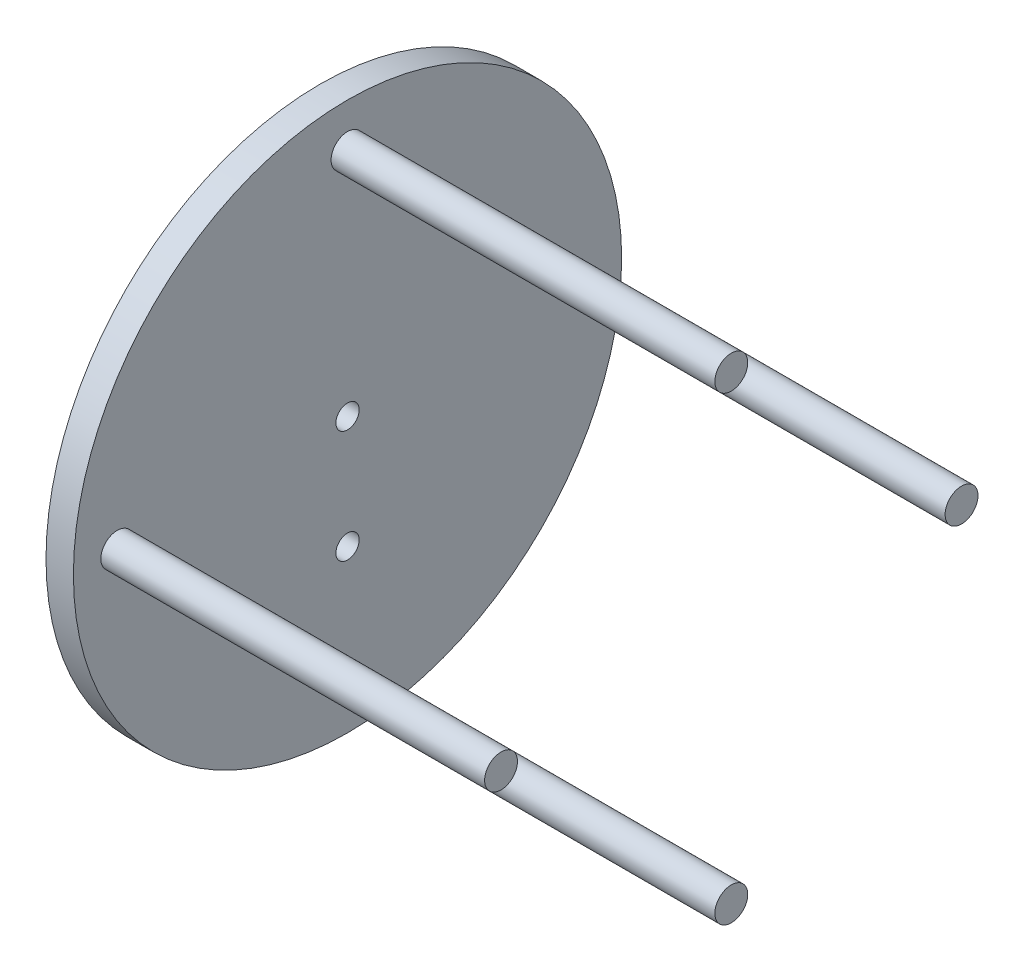
SolidWorks part; units mm, degrees
ref_plane "Plan de face" through (0, 0, 0) normal (0, 0, 1) x (1, 0, 0)
ref_plane "Plan de dessus" through (0, 0, 0) normal (0, 1, 0) x (1, 0, 0)
ref_plane "Plan de droite" through (0, 0, 0) normal (1, 0, 0) x (0, 0, -1)
sketch "Esquisse1" plane through (0, 0, 0) normal (1, 0, 0) x (0, 0, -1)
  circle A0 centre (0, 0) radius 50
  dimension "D1" = 100
extrude "Boss.-Extru.1" add sketch "Esquisse1" along normal blind 5
sketch "Esquisse2" plane through (5, 0, 0) normal (1, 0, 0) x (0, 0, -1)
  line L0 (0, 0) -> (50, 0) construction
  line L1 (0, 0) -> (-50, 0) construction
  line L2 (0, 0) -> (0, 50) construction
  line L3 (0, 0) -> (0, -50) construction
  circle A0 centre (0, 0) radius 50 construction
  circle A1 centre (-42, 0) radius 3
  circle A2 centre (42, 0) radius 3
  circle A3 centre (0, -42) radius 3
  circle A4 centre (0, 42) radius 3
  dimension "D3" = 6
  dimension "D4" = 6
  dimension "D7" = 6
  dimension "D8" = 6
  dimension "D1" = 8
  dimension "D2" = 8
  dimension "D5" = 8
  dimension "D6" = 8
extrude "Boss.-Extru.3" add sketch "Esquisse2" along normal blind 70
sketch "Esquisse3" plane through (5, 0, 0) normal (1, 0, 0) x (0, 0, -1)
  line L0 (0, 0) -> (0, -50) construction
  circle A0 centre (0, 0) radius 2.125
  circle A1 centre (0, 0) radius 50 construction
  circle A2 centre (0, -20.5478) radius 2.125
  dimension "D1" = 4.25
  dimension "D2" = 4.25
extrude "Enlèv. mat.-Extru.2" cut sketch "Esquisse3" against normal blind 70
